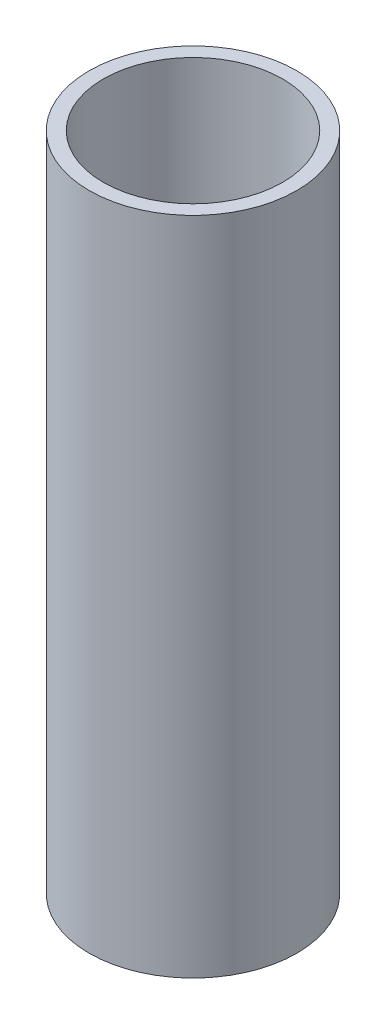
SolidWorks part; units mm, degrees
ref_plane "Front Plane" through (0, 0, 0) normal (0, 0, 1) x (1, 0, 0)
ref_plane "Top Plane" through (0, 0, 0) normal (0, 1, 0) x (1, 0, 0)
ref_plane "Right Plane" through (0, 0, 0) normal (1, 0, 0) x (0, 0, -1)
sketch "Sketch3" plane through (0, 0, 0) normal (0, 1, 0) x (1, 0, 0)
  circle A0 centre (0, 0) radius 11
extrude "Boss-Extrude1" add sketch "Sketch3" along normal blind 70
sketch "Sketch4" plane through (0, 70, 0) normal (0, 1, 0) x (1, 0, 0)
  circle A0 centre (0, 0) radius 2.8
extrude "Cut-Extrude1" cut sketch "Sketch4" against normal blind 70
sketch "Sketch5" plane through (0, 0, 0) normal (0, -1, 0) x (-1, 0, 0)
  circle A0 centre (0, 0) radius 9.5
extrude "Cut-Extrude2" cut sketch "Sketch5" against normal blind 33.5
sketch "Sketch6" plane through (0, 70, 0) normal (0, 1, 0) x (1, 0, 0)
  circle A0 centre (0, 0) radius 9.5
extrude "Cut-Extrude3" cut sketch "Sketch6" against normal blind 33.5 contours A0
